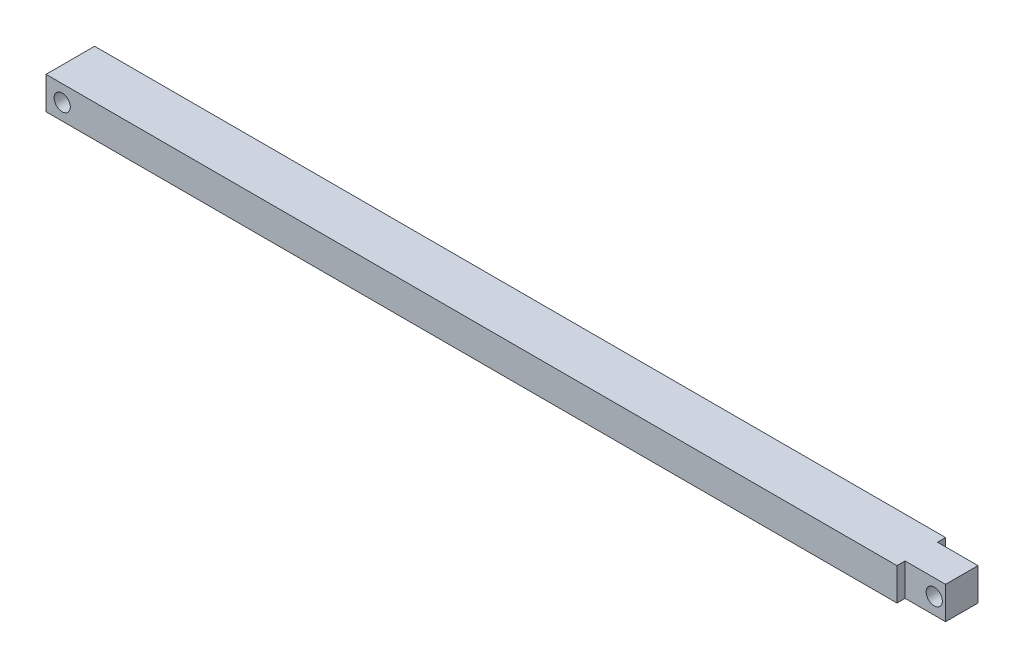
SolidWorks part; units mm, degrees
ref_plane "Front Plane" through (0, 0, 0) normal (0, 0, 1) x (1, 0, 0)
ref_plane "Top Plane" through (0, 0, 0) normal (0, 1, 0) x (1, 0, 0)
ref_plane "Right Plane" through (0, 0, 0) normal (1, 0, 0) x (0, 0, -1)
sketch "Sketch1" plane through (0, 0, 0) normal (0, 0, 1) x (1, 0, 0)
  line L0 (0, 10) -> (550, 10) construction
  line L1 (0, 0) -> (550, 0)
  line L2 (0, 0) -> (0, 20)
  line L3 (0, 20) -> (550, 20)
  line L4 (550, 0) -> (550, 20)
  circle A0 centre (10, 10) radius 5
  circle A1 centre (543, 10) radius 5
  dimension "D3" = 10
  dimension "D4" = 7
  dimension "D1" = 20
  dimension "D2" = 550
extrude "Boss-Extrude1" add sketch "Sketch1" against normal blind 30
sketch "Sketch3" plane through (0, 20, 0) normal (0, 1, 0) x (1, 0, 0)
  line L0 (550, 15) -> (0, 15) construction
  line L1 (550, 30) -> (550, 0) construction
  line L2 (0, -55) -> (0, 55) construction
  line L3 (550, 5) -> (525, 5)
  line L4 (550, 30) -> (525, 30)
  line L5 (550, 30) -> (550, 25)
  line L6 (550, 25) -> (525, 25)
  line L7 (525, 30) -> (525, 25)
  line L8 (525, 0) -> (525, 5)
  line L9 (550, 0) -> (525, 0)
  line L10 (550, 0) -> (550, 5)
  dimension "D1" = 25
  dimension "D2" = 5
extrude "Cut-Extrude2" cut sketch "Sketch3" against normal through all
